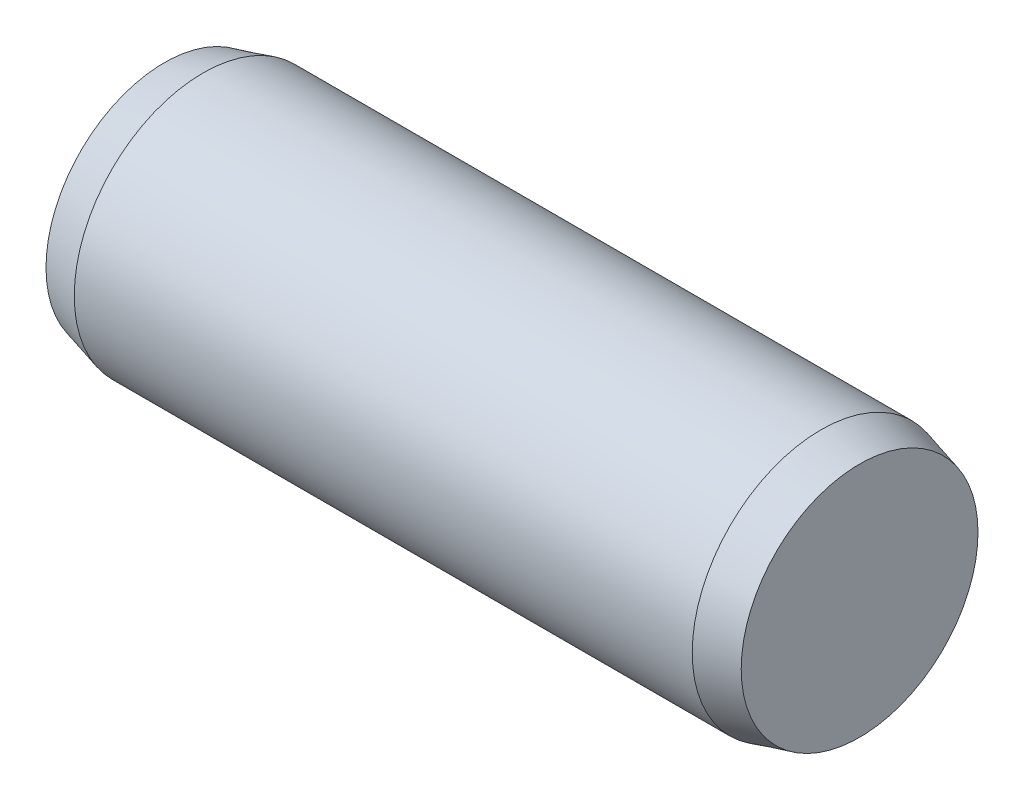
SolidWorks part; units mm, degrees
ref_plane "Front Plane" through (0, 0, 0) normal (0, 0, 1) x (1, 0, 0)
ref_plane "Top Plane" through (0, 0, 0) normal (0, 1, 0) x (1, 0, 0)
ref_plane "Right Plane" through (0, 0, 0) normal (1, 0, 0) x (0, 0, -1)
sketch "Sketch1" plane through (0, 0, 0) normal (0, 0, 1) x (1, 0, 0)
  line L0 (-6, 0) -> (6, 0) construction
  line L1 (6, 2.5) -> (6, -2.5) construction
  line L2 (-6, 2.5) -> (-6, -2.5) construction
  line L3 (6.75, 2.5) -> (6.75, -2.5) construction
  line L4 (-6.75, 2.5) -> (-6.75, -2.5) construction
  line L5 (-6, 0) -> (-6.75, 0) construction
  line L6 (6, 0) -> (6.75, 0) construction
  dimension "D1" = 0.75
  dimension "Dia" = 5
  dimension "Length" = 12
  dimension "C" = 0.75
sketch "Sketch2" plane through (0, 0, 0) normal (1, 0, 0) x (0, 0, -1)
  circle A0 centre (0, 0) radius 2.5
extrude "Extrude1" add sketch "Sketch2" against normal up to vertex (6 mm away) and the other way up to vertex (6 mm away) up to point (-6, 2.5, 0) other way up to point (6, 2.5, 0)
sketch "Sketch3" plane through (6, 0, 0) normal (1, 0, 0) x (0, 0, -1)
  circle A1 centre (0, 0) radius 2.5
  circle A2 centre (0, 0) radius 2.5
  dimension "D1" = 0
extrude "Extrude2" add sketch "Sketch3" along normal up to vertex (0.75 mm away) draft 15 up to point (6.75, 0, 0)
sketch "Sketch4" plane through (-6, 0, 0) normal (-1, 0, 0) x (0, 0, 1)
  circle A1 centre (0, 0) radius 2.5
  circle A2 centre (0, 0) radius 2.5
  dimension "D1" = 0
extrude "Extrude3" add sketch "Sketch4" along normal up to vertex (0.75 mm away) draft 15 up to point (-6.75, 0, 0)
equation "\"D1@Sketch1\" = \"C@Sketch1\""
